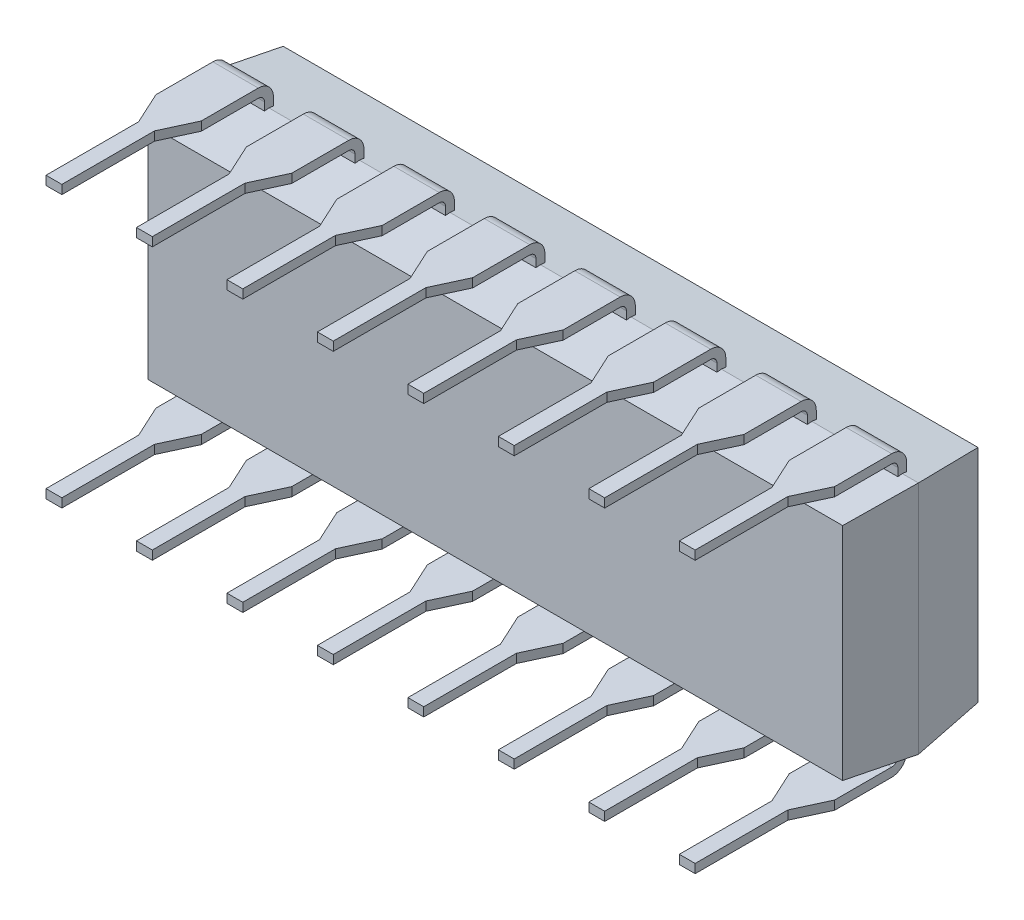
SolidWorks part; units mm, degrees
ref_plane "Plano frontal" through (0, 0, 0) normal (0, 0, 1) x (1, 0, 0)
ref_plane "Plano superior" through (0, 0, 0) normal (0, 1, 0) x (1, 0, 0)
ref_plane "Plano direito" through (0, 0, 0) normal (1, 0, 0) x (0, 0, -1)
sketch "Esboço1" plane through (0, 0, 0) normal (1, 0, 0) x (0, 0, -1)
  line L0 (0.9, 3.1) -> (0.9, -3.1)
  line L1 (0.9, -3.1) -> (2.8, -3.3)
  line L2 (2.8, -3.3) -> (4.7, -3.1)
  line L3 (4.7, -3.1) -> (4.7, 3.1)
  line L4 (4.7, 3.1) -> (2.8, 3.3)
  line L5 (2.8, 3.3) -> (0.9, 3.1)
  line L6 (2.8, 3.3) -> (2.8, -3.3) construction
  line L7 (4.7, 0) -> (2.8, 0) construction
  line L8 (2.8, 0) -> (0.9, 0) construction
  line L9 (0.9, 0) -> (0, 0) construction
  dimension "D1" = 6.6
  dimension "D2" = 6.2
  dimension "D3" = 3.8
  dimension "D4" = 0.9
extrude "Ressalto-extrusão1" add sketch "Esboço1" along normal mid plane 19.96
sketch "Esboço3" plane through (0, 0, 0) normal (0, 1, 0) x (1, 0, 0)
  line L0 (-9.98, 2.8) -> (-9.7499, 4.7268)
  line L1 (-9.7499, 4.7268) -> (-10.9163, 4.7268)
  line L2 (-10.9163, 4.7268) -> (-10.9163, 0.8732)
  line L3 (-10.9163, 0.8732) -> (-9.7499, 0.8732)
  line L4 (-9.7499, 0.8732) -> (-9.98, 2.8)
  line L5 (-10.9163, 2.8) -> (-9.98, 2.8) construction
  line L6 (-9.98, 0.9) -> (-9.98, 2.8) construction
  dimension "D1" = 6.81
  dimension "D2" = 3.8537
  dimension "D3" = 1.1665
extrude "Corte-extrusão2" cut sketch "Esboço3" against normal mid plane 7.1
mirror "Espelhar1" about plane through (0, 0, 0) normal (1, 0, 0) of "Corte-extrusão2"
sketch "Esboço8" plane through (0, 0, -4.7) normal (0, 0, -1) x (-1, 0, 0)
  line L0 (9.7531, -3.1) -> (9.7531, 3.1) construction
  circle A0 centre (9.7531, 0) radius 1
  dimension "D1" = 2
extrude "Corte-extrusão5" cut sketch "Esboço8" against normal blind 0.5
ref_plane "Plano1" through (0, 3.3, 0) normal (0, 1, 0) x (1, 0, 0)
sketch "Esboço6" plane through (0, 3.3, 0) normal (0, 1, 0) x (1, 0, 0)
  line L0 (-8.2525, 2.8) -> (0, 2.8) construction
  line L1 (-9.5275, 2.925) -> (-8.2525, 2.925)
  line L2 (-9.5275, 2.925) -> (-9.5275, 2.675)
  line L3 (-9.5275, 2.675) -> (-8.2525, 2.675)
  line L4 (-8.2525, 2.925) -> (-8.2525, 2.675)
  line L5 (9.98, 2.8) -> (-9.98, 2.8) construction
  line L6 (-8.89, 2.925) -> (-8.89, 2.675) construction
  dimension "D1" = 0.25
  dimension "D2" = 1.275
  dimension "D3" = 1.09
extrude "Ressalto-extrusão2" add sketch "Esboço6" along normal mid plane 0.05
sketch "Esboço7" plane through (0, 3.325, 0) normal (0, 1, 0) x (1, 0, 0)
  line L0 (-9.5275, 2.925) -> (-9.5275, 2.675) construction
  line L1 (-8.2525, 2.925) -> (-9.5275, 2.925) construction
  line L2 (-8.2525, 2.675) -> (-8.2525, 2.925) construction
  line L3 (-9.5275, 2.675) -> (-8.2525, 2.675) construction
  line L4 (-9.5275, 2.925) -> (-9.5275, 2.675)
  line L5 (-8.2525, 2.925) -> (-9.5275, 2.925)
  line L6 (-8.2525, 2.675) -> (-8.2525, 2.925)
  line L7 (-9.5275, 2.675) -> (-8.2525, 2.675)
  line L8 (-9.5275, 2.8) -> (-8.2525, 2.8) construction
sketch3d "3DSketch1"
  line L0 (-8.89, 3.325, -2.8) -> (-8.89, 3.51, -2.8)
  line L1 (-8.89, 3.325, -2.8) -> (-8.89, 0, -2.8) construction
  line L2 (-9.5275, 3.325, -2.8) -> (-8.2525, 3.325, -2.8) construction
  line L3 (-8.89, 3.81, -2.5) -> (-8.89, 3.81, 0)
  line L4 (-8.89, 0, -2.8) -> (0, 0, 0) construction
  arc A0 (-8.89, 3.51, -2.8) -> (-8.89, 3.81, -2.5) centre (-8.89, 3.51, -2.5) ccw
  point P5 (-8.59, 3.51, -2.5)
  dimension "D3" = 0.3
  dimension "D1" = 2.8
  dimension "D2" = 3.81
sweep "Varredura1" add profiles "Esboço7" path "3DSketch1"
sketch "Esboço9" plane through (0, 3.935, 0) normal (0, 1, 0) x (1, 0, 0)
  line L0 (-9.1125, 0) -> (-9.5275, 0.9)
  line L1 (-8.2525, 0) -> (-9.5275, 0) construction
  line L3 (-9.5275, 2.5) -> (-9.5275, 0) construction
  line L4 (-9.5275, 0.9) -> (-9.5275, -0.2)
  line L5 (-9.5275, -0.2) -> (-8.2525, -0.2)
  line L6 (-8.2525, -0.2) -> (-8.2525, 0.9)
  line L7 (-8.2525, 2.5) -> (-8.2525, 0) construction
  line L8 (-8.2525, 0.9) -> (-8.6675, 0)
  line L9 (-8.6675, 0) -> (-9.1125, 0)
  line L10 (-8.89, 0) -> (-8.89, 2.5) construction
  line L11 (-8.2525, 2.5) -> (-9.5275, 2.5) construction
  dimension "D1" = 0.9
  dimension "D2" = 0.445
  dimension "D3" = 0.2
extrude "Corte-extrusão6" cut sketch "Esboço9" against normal up to next
sketch "Esboço10" plane through (0, 0, 0) normal (0, 0, 1) x (1, 0, 0)
  line L0 (-8.6675, 3.935) -> (-9.1125, 3.935) construction
  line L1 (-9.1125, 3.935) -> (-9.1125, 3.685) construction
  line L2 (-9.1125, 3.685) -> (-8.6675, 3.685) construction
  line L3 (-8.6675, 3.685) -> (-8.6675, 3.935) construction
  line L4 (-8.6675, 3.935) -> (-9.1125, 3.935)
  line L5 (-9.1125, 3.935) -> (-9.1125, 3.685)
  line L6 (-9.1125, 3.685) -> (-8.6675, 3.685)
  line L7 (-8.6675, 3.685) -> (-8.6675, 3.935)
extrude "Ressalto-extrusão3" add sketch "Esboço10" along normal blind 2.6
mirror "Espelhar2" about plane through (0, 0, 0) normal (0, 1, 0) of "Ressalto-extrusão3", "Corte-extrusão6", "Varredura1", "Ressalto-extrusão2"
pattern_linear "Padrão linear1" count 8 spacing 2.54 along (1, 0, 0) of "Ressalto-extrusão2", "Varredura1", "Corte-extrusão6", "Ressalto-extrusão3", "Espelhar2"
